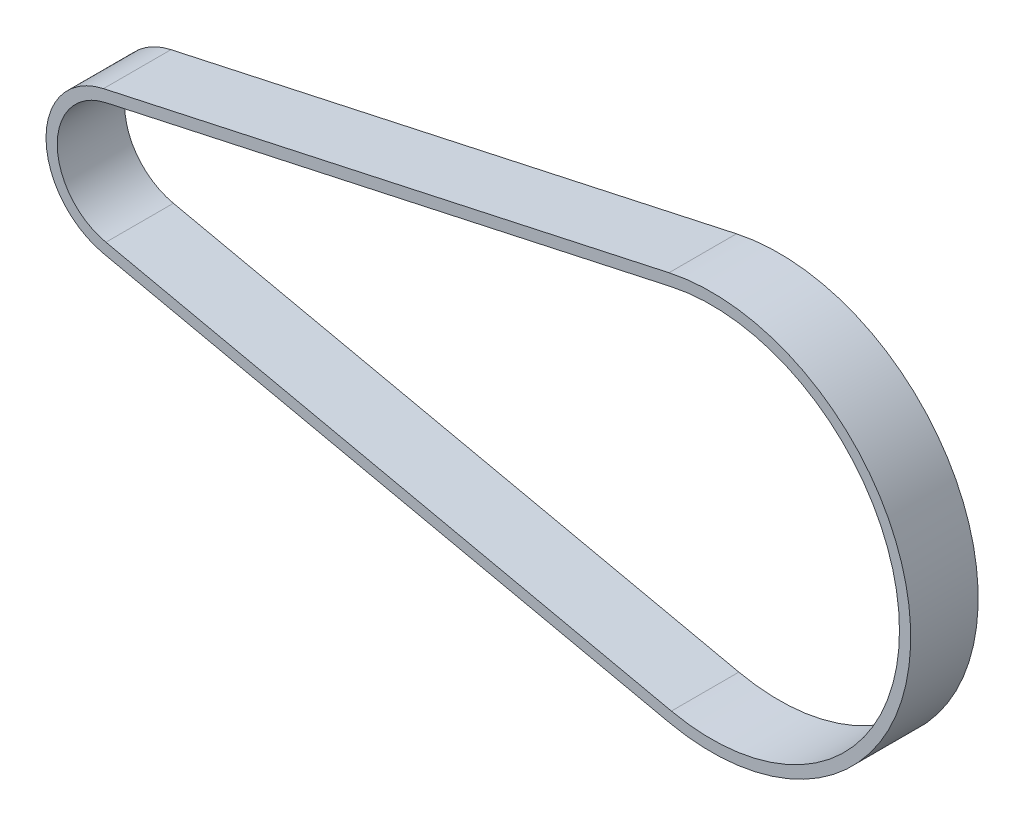
SolidWorks part; units mm, degrees
material "HYPALON"
ref_plane "Alzado" through (0, 0, 0) normal (0, 0, 1) x (1, 0, 0)
ref_plane "Planta" through (0, 0, 0) normal (0, 1, 0) x (1, 0, 0)
ref_plane "Vista lateral" through (0, 0, 0) normal (1, 0, 0) x (0, 0, -1)
sketch "Croquis1" plane through (0, 0, 0) normal (0, 0, 1) x (1, 0, 0)
  line L0 (-1.1715, 5.3738) -> (49.1136, 16.3363)
  line L1 (-1.1715, -5.3738) -> (49.1136, -16.3363)
  line L2 (-1.3845, 6.3508) -> (48.9006, 17.3133)
  line L3 (-1.3845, -6.3508) -> (48.9006, -17.3133)
  arc A0 (-1.1715, 5.3738) -> (-1.1715, -5.3738) centre (0, 0) ccw
  arc A1 (49.1136, -16.3363) -> (49.1136, 16.3363) centre (52.675, 0) ccw
  arc A2 (48.9006, -17.3133) -> (48.9006, 17.3133) centre (52.675, 0) ccw
  arc A3 (-1.3845, 6.3508) -> (-1.3845, -6.3508) centre (0, 0) ccw
  dimension "D1" = 11
  dimension "D2" = 33.44
  dimension "D3" = 52.675
  dimension "D4" = 1
extrude "Saliente-Extruir1" add sketch "Croquis1" along normal blind 6
